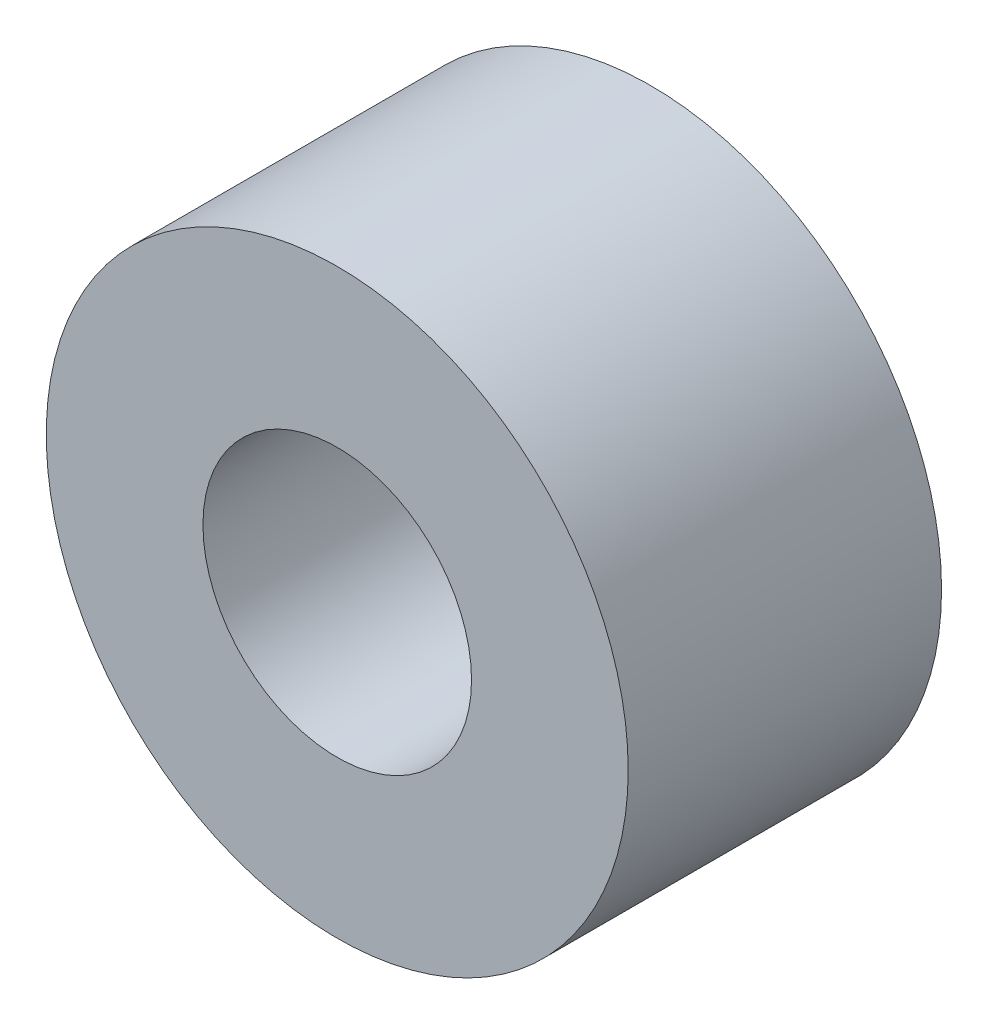
SolidWorks part; units mm, degrees
ref_plane "Front Plane" through (0, 0, 0) normal (0, 0, 1) x (1, 0, 0)
ref_plane "Top Plane" through (0, 0, 0) normal (0, 1, 0) x (1, 0, 0)
ref_plane "Right Plane" through (0, 0, 0) normal (1, 0, 0) x (0, 0, -1)
sketch "Sketch1" plane through (0, 0, 0) normal (0, 0, 1) x (1, 0, 0)
  circle A0 centre (0, 0) radius 6.5
  circle A1 centre (0, 0) radius 3
  dimension "D1" = 13
  dimension "D2" = 6
extrude "Boss-Extrude1" add sketch "Sketch1" along normal blind 7
equation "\"roller_radius\"= 6.5"
equation "\"eccentricity\"= \"roller_radius\" * 0.325"
equation "\"outer_radius\"= 40"
equation "\"eccentric_shaft_radius\"= 16"
equation "\"rotor_width\"= 10"
equation "\"housing_depth\"= 40"
equation "\"bottom_depth\"= 5"
equation "\"roller_bearing_OD\"= \"roller_radius\" * 2"
equation "\"roller_bearing_ID\"= 6"
equation "\"eccentric_bearing_ID\"= 6"
equation "\"eccentric_bearing_OD\"= 15"
equation "\"roller_bearing_height\"= 5"
equation "\"eccentric_bearing_height\"= 5"
equation "\"bottom_bearing_ID\"= 15"
equation "\"bottom_bearing_OD\"= 32"
equation "\"bottom_bearing_height\"= 9"
equation "\"distance_to_output_rotor_holes\"= 20"
equation "\"D1@Sketch1\"=\"roller_bearing_OD\""
equation "\"D2@Sketch1\"=\"roller_bearing_ID\""
equation "\"output_bearing_ID\" = 25"
equation "\"output_bearing_OD\" = 37"
equation "\"output_bearing_height\" = 7"
equation "\"number_of_rollers\" = 15"
equation "\"housing_height\" = 27"
equation "\"spacer_1\" = 7"
equation "\"spacer_2\" = 2.5"
equation "\"spacer_3\" = 7.5"
equation "\"roller_pin_depth\" = 5"
equation "\"D1@Boss-Extrude1\"=\"spacer_1\""
